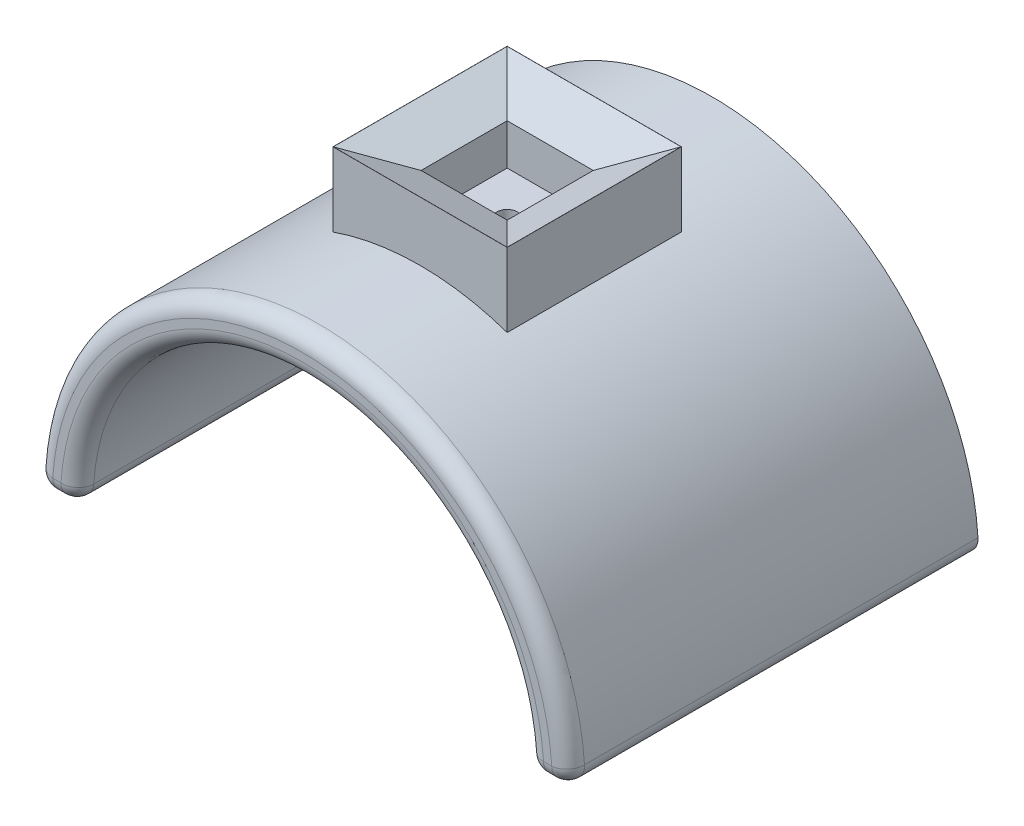
SolidWorks part; units mm, degrees
ref_plane "Top Plane" through (0, 0, 0) normal (0, 0, 1) x (1, 0, 0)
ref_plane "Right Plane" through (0, 0, 0) normal (0, 1, 0) x (1, 0, 0)
ref_plane "Front Plane" through (0, 0, 0) normal (1, 0, 0) x (0, 0, -1)
sketch "Sketch1" plane through (0, 0, 0) normal (0, 0, 1) x (1, 0, 0)
  line L0 (-65, 0) -> (-55, 0)
  line L1 (55, 0) -> (65, 0)
  line L2 (-55, 0) -> (55, 0) construction
  arc A0 (-55, 0) -> (55, 0) centre (0, 0) cw
  arc A1 (-65, 0) -> (65, 0) centre (0, 0) cw
  dimension "D1" = 55
  dimension "D2" = 10
extrude "Boss-Extrude1" add sketch "Sketch1" along normal mid plane 100
sketch "Sketch2" plane through (0, 0, 0) normal (0, 0, 1) x (1, 0, 0)
  line L0 (-21.25, 61.4283) -> (-21.25, 79.4283)
  line L1 (-21.25, 79.4283) -> (21.25, 79.4283)
  line L2 (21.25, 79.4283) -> (21.25, 61.4283)
  line L3 (0, 65) -> (0, 0) construction
  line L4 (0, 65) -> (0, 79.4283) construction
  arc A0 (-21.25, 61.4283) -> (21.25, 61.4283) centre (0, 0) cw
  arc A1 (65, 0) -> (-65, 0) centre (0, 0) ccw construction
  dimension "D1" = 42.5
  dimension "D2" = 18
extrude "Boss-Extrude2" add sketch "Sketch2" along normal mid plane 42.5
fillet "Fillet1" radius 4 4 edges at (55, 0, 0) (65, 0, 0) (-65, 0, 0) (-55, 0, 0)
fillet "Fillet2" radius 4 8 edges at (63.7884, 1.2659, 50) (59.8665, 0, 50) (56.1334, 1.0773, 50) (0, 55, 50) (-56.1334, 1.0773, 50) (-59.8665, 0, 50) (-63.7884, 1.2659, 50) (0, 65, 50)
sketch "Sketch3" plane through (0, 79.4283, 0) normal (0, 1, 0) x (1, 0, 0)
  line L0 (10.5, -10.5) -> (-10.5, 10.5) construction
  line L1 (10.5, -10.5) -> (-10.5, -10.5)
  line L2 (10.5, -10.5) -> (10.5, 10.5)
  line L3 (10.5, 10.5) -> (-10.5, 10.5)
  line L4 (-10.5, -10.5) -> (-10.5, 10.5)
  point P4 (0, 0)
  dimension "D1" = 21
extrude "Cut-Extrude1" cut sketch "Sketch3" against normal blind 15
chamfer "Chamfer1" distance 5 angle 65 4 edges at (-10.5, 79.4283, 0) (0, 79.4283, 10.5) (10.5, 79.4283, 0) (0, 79.4283, -10.5)
sketch "Sketch4" plane through (0, 64.4283, 0) normal (0, 1, 0) x (1, 0, 0)
  circle A0 centre (0, 0) radius 2.5
  dimension "D1" = 5
extrude "Cut-Extrude2" cut sketch "Sketch4" against normal through all
sketch "Sketch5" plane through (0, 64.4283, 0) normal (0, 1, 0) x (1, 0, 0)
  circle A0 centre (0, 0) radius 5
  dimension "D1" = 10
extrude "Cut-Extrude3" cut sketch "Sketch5" against normal through all from offset 5
